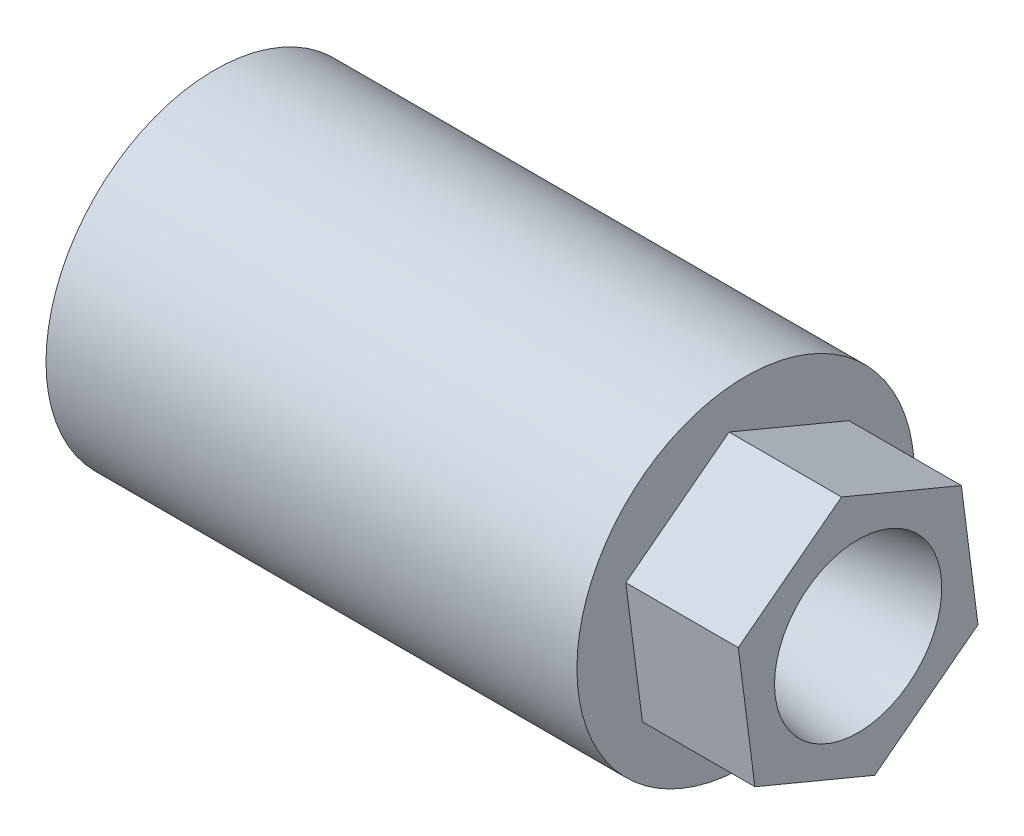
SolidWorks part; units mm, degrees
ref_plane "Front Plane" through (0, 0, 0) normal (0, 0, 1) x (1, 0, 0)
ref_plane "Top Plane" through (0, 0, 0) normal (0, 1, 0) x (1, 0, 0)
ref_plane "Right Plane" through (0, 0, 0) normal (1, 0, 0) x (0, 0, -1)
sketch "Sketch1" plane through (0, 0, 0) normal (0, 0, 1) x (1, 0, 0)
  line L0 (0, 0) -> (10.9228, 0) construction
  line L1 (0.278, 2.081) -> (10.9228, 5.9554) construction
  line L2 (-2.1553, 2.9247) -> (-4.048, 4.8174)
  line L3 (-25.4, 5.7474) -> (-25.4, 9.525)
  line L4 (-6.293, 5.7474) -> (-25.4, 5.7474)
  line L5 (-25.4, 9.525) -> (-1.7772, 9.525)
  line L6 (10.9228, 9.525) -> (10.9228, 4.7219)
  line L7 (10.9228, 4.7219) -> (12.711, 4.9733) construction
  line L8 (-1.7772, 9.525) -> (10.9228, 9.525)
  arc A0 (-2.1553, 2.9247) -> (0, 2.032) centre (0, 5.08) ccw
  arc A1 (0, 2.032) -> (0.278, 2.081) centre (0, 2.8448) ccw
  arc A2 (-4.048, 4.8174) -> (-6.293, 5.7474) centre (-6.293, 2.5724) ccw
  parabola Q0 (10.9228, 4.7219) -> (0.278, 2.081) focus (9.0524, -22.0264) apex (0.278, 2.081)
  dimension "D3" = 3.048
  dimension "D4" = 0.8128
  dimension "D11" = 3.175
  dimension "D12" = 8
  dimension "D1" = 2.032
  dimension "D2" = 10.9228
  dimension "D5" = 4.7219
  dimension "D6" = 20
  dimension "D7" = 45
  dimension "D8" = 5.7474
  dimension "D9" = 25.4
  dimension "D10" = 9.525
  dimension "D13" = 12.7
revolve "Revolve1" add sketch "Sketch1" angle 360 about L0
sketch "Sketch3" plane through (10.9228, 0, 0) normal (1, 0, 0) x (0, 0, -1)
  line L1 (0.9374, -7.2722) -> (6.7666, -2.8242)
  line L2 (6.7666, -2.8242) -> (5.8292, 4.4479)
  line L3 (5.8292, 4.4479) -> (-0.9374, 7.2722)
  line L4 (-0.9374, 7.2722) -> (-6.7666, 2.8242)
  line L5 (-6.7666, 2.8242) -> (-5.8292, -4.4479)
  line L6 (-5.8292, -4.4479) -> (0.9374, -7.2722)
  circle A0 centre (0, 0) radius 6.35 construction
  circle M7 centre (0, 0) radius 9.525
  dimension "D1" = 12.7
extrude "Cut-Extrude2" cut sketch "Sketch3" against normal blind 6.35 contours L6 L5 L4 L3 L2 L1 M7
equation "\"D3@Sketch1\"= 1.5 * \"D1@Sketch1\""
equation "\"D4@Sketch1\"=.4 * \"D1@Sketch1\""
equation "\"D5@Sketch1\"=\"D1@Sketch1\" * ( 5.4 ) ^ .5"
equation "\"D8@Sketch1\"=\"D1@Sketch1\" * ( 8 ) ^ .5"
equation "\"er\"= 4"
